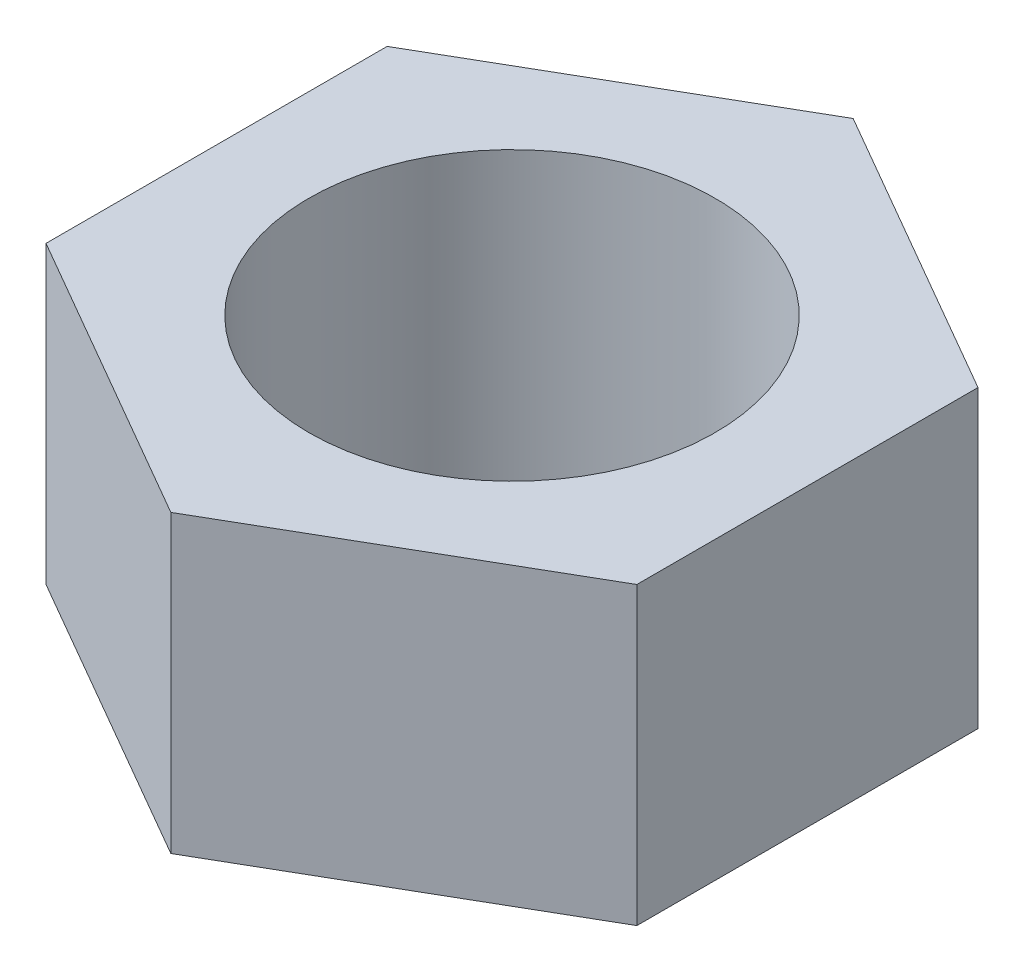
SolidWorks part; units mm, degrees
ref_plane "Front Plane" through (0, 0, 0) normal (0, 0, 1) x (1, 0, 0)
ref_plane "Top Plane" through (0, 0, 0) normal (0, 1, 0) x (1, 0, 0)
ref_plane "Right Plane" through (0, 0, 0) normal (1, 0, 0) x (0, 0, -1)
sketch "Sketch1" plane through (0, 0, 0) normal (0, 1, 0) x (1, 0, 0)
  line L1 (0, 4.6188) -> (-4, 2.3094)
  line L2 (-4, 2.3094) -> (-4, -2.3094)
  line L3 (-4, -2.3094) -> (0, -4.6188)
  line L4 (0, -4.6188) -> (4, -2.3094)
  line L5 (4, -2.3094) -> (4, 2.3094)
  line L6 (4, 2.3094) -> (0, 4.6188)
  circle A0 centre (0, 0) radius 4 construction
  point P1 (0, 0)
  dimension "D1" = 8
extrude "Body" add sketch "Sketch1" along normal blind 4
hole_wizard "M5 Clearance Hole1" positions "Sketch2" profile "Sketch3" hole size "M5" standard "ANSI Metric" end condition through all
sketch "Sketch2" plane through (0, 4, 0) normal (0, 1, 0) x (1, 0, 0)
  point P0 (0, 0)
sketch "Sketch3" plane through (0, 4, 0) normal (1, 0, 0) x (0, 0, 1)
  line L0 (0, 0) -> (0, 4)
  line L1 (0, 4) -> (2.75, 4)
  line L2 (2.75, 4) -> (2.75, 0)
  line L5 (2.75, 0) -> (0, 0)
  line L11 (0, -6.35) -> (0, 107.95) construction
  dimension "Thru Hole Dia." = 5.5
  dimension "Thru Hole Depth" = 4
